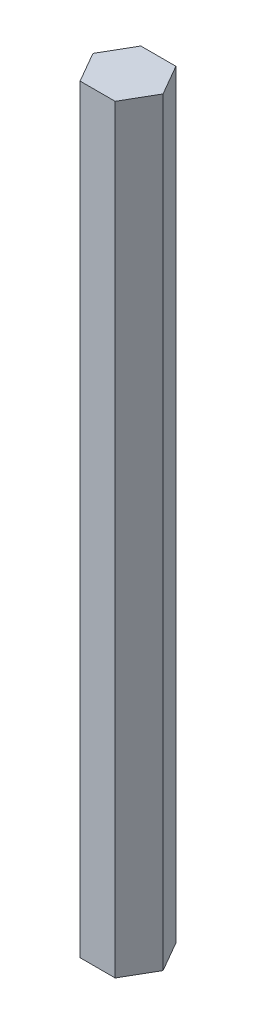
SolidWorks part; units mm, degrees
ref_plane "Front Plane" through (0, 0, 0) normal (0, 0, 1) x (1, 0, 0)
ref_plane "Top Plane" through (0, 0, 0) normal (0, 1, 0) x (1, 0, 0)
ref_plane "Right Plane" through (0, 0, 0) normal (1, 0, 0) x (0, 0, -1)
sketch "Sketch1" plane through (0, 0, 0) normal (0, 1, 0) x (1, 0, 0)
  line L1 (4.6188, 0) -> (2.3094, 4)
  line L2 (2.3094, 4) -> (-2.3094, 4)
  line L3 (-2.3094, 4) -> (-4.6188, 0)
  line L4 (-4.6188, 0) -> (-2.3094, -4)
  line L5 (-2.3094, -4) -> (2.3094, -4)
  line L6 (2.3094, -4) -> (4.6188, 0)
  circle A0 centre (0, 0) radius 4 construction
  dimension "D1" = 8
extrude "Boss-Extrude1" add sketch "Sketch1" along normal blind 100
